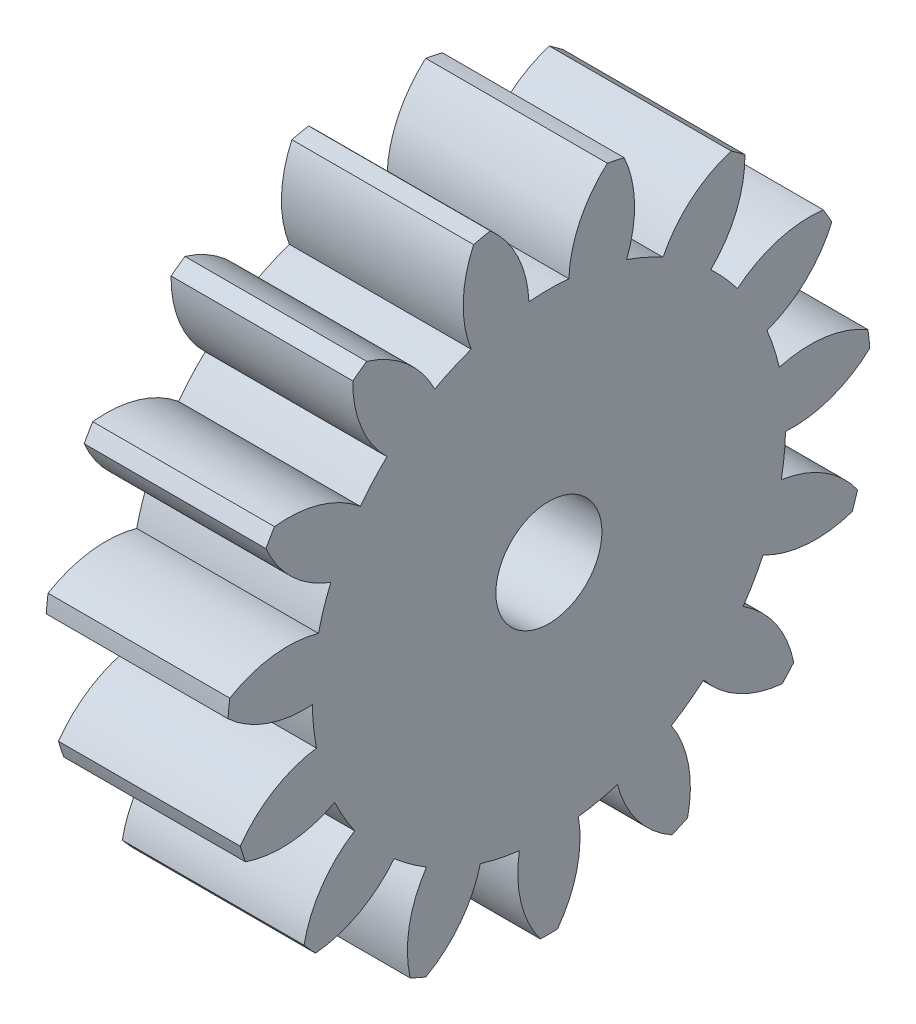
SolidWorks part; units mm, degrees
ref_plane "Plane1" through (0, 0, 0) normal (0, 0, 1) x (1, 0, 0)
ref_plane "Plane2" through (0, 0, 0) normal (0, 1, 0) x (1, 0, 0)
ref_plane "Plane3" through (0, 0, 0) normal (1, 0, 0) x (0, 0, -1)
other "Configuration Table"
sketch "HoldingSke" plane through (0, 0, 0) normal (0, 1, 0) x (1, 0, 0)
  line L0 (0, 0) -> (0.3864, -0.1035)
  line L1 (-15, 0) -> (100, 0) construction
  line L2 (0, 0) -> (-2.1039, 2.3779)
  line L3 (0, 0) -> (-11.863, 4.5341)
  line L4 (0, 0) -> (8.3417, 2.2352)
  line L5 (0, 0) -> (-46.8476, -17.4728)
  line L6 (0, 0) -> (-9.9476, -6.7116)
  line L7 (-2.1039, 2.3779) -> (8.6586, 51.2059)
  line L8 (-76.2, 54.61) -> (-75.2, 54.61)
  line L9 (-71.009, 38.7566) -> (-53.1078, 45.2721)
  line L10 (-76.2, 71.12) -> (104.1128, 71.12)
  line L11 (0, 0) -> (-12, 0)
  line L12 (-76.2, 101.6) -> (-76.113, 101.6)
  line L13 (24.9733, 27.94) -> (52.9518, 28.4284)
  line L14 (24.9733, 27.94) -> (24.9743, 27.94)
  line L15 (24.9733, 27.94) -> (100.4006, 29.5858)
  line L16 (-63.627, -2.5) -> (-12.827, -2.5)
  circle A0 centre (0, 0) radius 3.5
  circle A1 centre (0, 0) radius 15.624
  circle A2 centre (0, 0) radius 37.5
  circle A3 centre (0, 0) radius 3.5
  dimension "Hub_dia" = 75
  dimension "Bore" = 7
  dimension "MBD" = 7
  dimension "Num_teeth" = 15
  dimension "Overall_len" = 50
  dimension "Show_teeth" = 15
  dimension "Thickness" = 12
  dimension "OAL" = 50.0001
  dimension "T_dim" = 1
  dimension "Ap" = 20
  dimension "H" = 19.05
  dimension "Pitch_radius" = 180.3128
  dimension "Width" = 12
  dimension "Addendum_fac" = 1
  dimension "Dedendum_fac" = 1.25
  dimension "Clearance_fac" = 0.25
  dimension "Dedendum_add" = 0.001
sketch "BasProSke" plane through (0, 0, 0) normal (0, 1, 0) x (1, 0, 0)
  line L0 (-10, 0) -> (60, 0) construction
  line L1 (0, 0) -> (0, 21.25)
  line L2 (0, 0) -> (12, 0)
  line L3 (12, 0) -> (12, 21.25)
  line L4 (12, 21.25) -> (0, 21.25)
  dimension "Thickness" = 12
revolve "Base-Revolve" add sketch "BasProSke" angle 360 about L0
sketch "TooCutSke" plane through (0, 0, 0) normal (1, 0, 0) x (0, 0, -1)
  line L1 (0, 0) -> (0, 107) construction
  line L2 (0, 0) -> (-2.112, 18.6307) construction
  line L3 (0, 0) -> (-7.7604, 36.5097) construction
  line L4 (-2.112, 18.6307) -> (-3.8802, 18.2548) construction
  arc A0 (1.3173, 15.5684) -> (-1.3173, 15.5684) centre (0, 0) ccw
  arc A1 (3.8889, 20.917) -> (-3.8889, 20.917) centre (0, 0) ccw
  circle A2 centre (0, 0) radius 18.75 construction
  circle A3 centre (0, 0) radius 17.6192 construction
  arc A4 (-1.3173, 15.5684) -> (-3.8889, 20.917) centre (-8.8109, 15.258) ccw
  arc A5 (3.8889, 20.917) -> (1.3173, 15.5684) centre (8.8109, 15.258) ccw
  dimension "Half_ang" = 12
extrude "ToothCut" cut sketch "TooCutSke" along normal through all
fillet "Breaks" [suppressed] radius 0.05
fillet "RootFillets" [suppressed] radius 0.626
pattern_circular "TeethCuts" count 15 every 24 about axis through (-10, 0, 0) along (1, 0, 0) of "ToothCut", "RootFillets", "Breaks"
sketch "HubNeaOneSke" plane through (0, 0, 0) normal (-1, 0, 0) x (0, 0, 1)
  circle A0 centre (0, 0) radius 15.624
extrude "HubNearOne" [suppressed] add sketch "HubNeaOneSke" along normal blind 38.0001
sketch "HubNeaBotSke" plane through (0, 0, 0) normal (-1, 0, 0) x (0, 0, 1)
  circle A0 centre (0, 0) radius 15.624
extrude "HubNearBoth" [suppressed] add sketch "HubNeaBotSke" along normal blind 19
ref_plane "FarPln" through (12, 0, 0) normal (1, 0, 0) x (0, 0, -1)
sketch "HubFarSke" plane through (12, 0, 0) normal (1, 0, 0) x (0, 0, -1)
  circle A0 centre (0, 0) radius 15.624
extrude "HubFar" [suppressed] add sketch "HubFarSke" along normal blind 19
sketch "BorSke" plane through (0, 0, 0) normal (1, 0, 0) x (0, 0, -1)
  circle A0 centre (0, 0) radius 3.5
  dimension "Diameter" = 7
extrude "Bore" cut sketch "BorSke" along normal mid plane 100.0001
sketch "KeySke" plane through (0, 0, 0) normal (1, 0, 0) x (0, 0, -1)
  line L0 (-1, 0) -> (-1, 4.5)
  line L1 (-1, 4.5) -> (1, 4.5)
  line L2 (1, 4.5) -> (1, 0)
  line L3 (0, 0) -> (0, 34) construction
  line L4 (-1, 0) -> (1, 0)
  dimension "Offset" = 4.5
  dimension "Width" = 2
extrude "Keyway" [suppressed] cut sketch "KeySke" along normal mid plane 100.0001
pattern_circular "Keyway2" [suppressed] count 2 every 90 about axis through (-10, 0, 0) along (1, 0, 0)
equation "' \"Module@HoldingSke\" = 6.35"
equation "' \"Num_teeth@HoldingSke\" = 12"
equation "' \"Ap@HoldingSke\" =  20"
equation "' \"Ap@HoldingSke\" = 20"
equation "' \"Width@HoldingSke\" = 0.5 * 25.4"
equation "' \"Hub_dia@HoldingSke\"= 1 * 25.4"
equation "' \"Hub_dia@HoldingSke\" = 1 * 25.4"
equation "' \"Overall_len@HoldingSke\" = 1.0 * 25.4"
equation "' \"Bore@HoldingSke\" = 0.75 * 25.4"
equation "' \"T_dim@HoldingSke\" = 0.1 * 25.4"
equation "' \"Width@KeySke\" = 0.25 * 25.4"
equation "' \"Show_teeth@HoldingSke\" = 13"
equation "' \"Backlash@HoldingSke\" = 0.009 * 25.4"
equation "' \"Addendum_fac@HoldingSke\" = 1.0"
equation "' \"Dedendum_fac@HoldingSke\" = 1.25"
equation "' \"Dedendum_add@HoldingSke\" = 0.00005 * 25.4"
equation "' \"Clearance_fac@HoldingSke\" = 0.25"
equation "\"Pitch@HoldingSke\" = 1 / \"Module@HoldingSke\""
equation "\"Overcut_dia@TooCutSke\" = (\"Num_teeth@HoldingSke\" + 2 * \"Addendum_fac@HoldingSke\") / \"Pitch@HoldingSke\" + 0.002 * 25.4"
equation "\"Pitch_dia@TooCutSke\" = \"Num_teeth@HoldingSke\" / \"Pitch@HoldingSke\""
equation "\"Base_dia@TooCutSke\" = \"Num_teeth@HoldingSke\" / \"Pitch@HoldingSke\" * cos((\"Ap@HoldingSke\"  * 3.14159265 / 180))"
equation "\"Root_dia@TooCutSke\" = (\"Num_teeth@HoldingSke\" + 2) / \"Pitch@HoldingSke\" - 2 * (\"Addendum_fac@HoldingSke\" + \"Dedendum_fac@HoldingSke\") / \"Pitch@HoldingSke\" - \"Dedendum_add@HoldingSke\" * 2"
equation "\"Half_ang@TooCutSke\" = 180 / \"Num_teeth@HoldingSke\""
equation "\"Half_CT@TooCutSke\" = \"Num_teeth@HoldingSke\" / \"Pitch@HoldingSke\" * sin((3.14159265 / 2 / \"Num_teeth@HoldingSke\")) / 2 - 7 * \"Backlash@HoldingSke\" / 4"
equation "\"Flank_rad@TooCutSke\" = \"Num_teeth@HoldingSke\" / \"Pitch@HoldingSke\" / 5"
equation "\"Radius@RootFillets\" = \"Clearance_fac@HoldingSke\" / \"Pitch@HoldingSke\" + \"Dedendum_add@HoldingSke\""
equation "\"Break_rad@Breaks\" = 0.02 / \"Pitch@HoldingSke\""
equation "\"Thickness@HoldingSke\" = \"Width@HoldingSke\""
equation "\"OAL@HoldingSke\" = \"Thickness@HoldingSke\""
equation "\"MHD@HoldingSke\" = (\"Num_teeth@HoldingSke\" + 2) / \"Pitch@HoldingSke\" - 2 * (\"Addendum_fac@HoldingSke\" + \"Dedendum_fac@HoldingSke\")  / \"Pitch@HoldingSke\" - \"Dedendum_add@HoldingSke\" * 2"
equation "\"MBD@HoldingSke\" = (\"Num_teeth@HoldingSke\" + 2) / \"Pitch@HoldingSke\" - 2 * (\"Addendum_fac@HoldingSke\" + \"Dedendum_fac@HoldingSke\")  / \"Pitch@HoldingSke\" - \"Dedendum_add@HoldingSke\" * 2 - 0.002 * 25.4"
equation "\"MHD@HoldingSke\" = ((sgn( \"MHD@HoldingSke\" - \"Hub_dia@HoldingSke\" )-1)*( \"MHD@HoldingSke\" - \"Hub_dia@HoldingSke\" ))/-2+ \"Hub_dia@HoldingSke\""
equation "\"MBD@HoldingSke\" = ((sgn( \"MBD@HoldingSke\" - \"Bore@HoldingSke\" )-1)*( \"MBD@HoldingSke\" - \"Bore@HoldingSke\" ))/-2+ \"Bore@HoldingSke\""
equation "\"OAL@HoldingSke\" = ((sgn( \"OAL@HoldingSke\" - \"Overall_len@HoldingSke\" )+1)*( \"OAL@HoldingSke\" - \"Overall_len@HoldingSke\" ))/2 + \"Overall_len@HoldingSke\" + 0.000002 * 25.4"
equation "\"Num_teeth@TeethCuts\" = int( \"Show_teeth@HoldingSke\" ) + 1"
equation "\"Num_teeth@TeethCuts\" = ((sgn( \"Num_teeth@TeethCuts\" - \"Num_teeth@HoldingSke\" )-1)*( \"Num_teeth@TeethCuts\" - \"Num_teeth@HoldingSke\" ))/-2+ \"Num_teeth@HoldingSke\""
equation "\"Num_teeth@TeethCuts\" = ((sgn( \"Num_teeth@TeethCuts\" - 2.0)+1)*( \"Num_teeth@TeethCuts\" - 2.0))/2 +2.0"
equation "\"Angle@TeethCuts\" = 360.0 / \"Num_teeth@HoldingSke\""
equation "\"Diameter@BasProSke\" = (\"Num_teeth@HoldingSke\" + 2 * \"Addendum_fac@HoldingSke\") / \"Pitch@HoldingSke\""
equation "\"Thickness@BasProSke\"  = \"Thickness@HoldingSke\""
equation "' \"Fillet_rad@BasProSke\" =  \"Thickness@HoldingSke\" * 0.05"
equation "' \"Fillet_rad@BasProSke\" = \"Thickness@HoldingSke\" * 0.05"
equation "\"MHD@HoldingSke\" = ((sgn( \"MHD@HoldingSke\" - \"Root_dia@TooCutSke\" )-1)*( \"MHD@HoldingSke\" - \"Root_dia@TooCutSke\" ))/-2+ \"Root_dia@TooCutSke\""
equation "\"Diameter@HubNeaOneSke\" = \"MHD@HoldingSke\""
equation "\"Length@HubNearOne\" = \"OAL@HoldingSke\" - \"Thickness@BasProSke\""
equation "\"Diameter@HubNeaBotSke\" = \"MHD@HoldingSke\""
equation "\"Length@HubNearBoth\" = ( \"OAL@HoldingSke\" - \"Thickness@BasProSke\" ) / 2.0"
equation "\"Thickness@FarPln\" = \"Thickness@BasProSke\""
equation "\"Diameter@HubFarSke\" = \"MHD@HoldingSke\""
equation "\"Length@HubFar\" = ( \"OAL@HoldingSke\" - \"Thickness@BasProSke\" ) / 2.0"
equation "\"Diameter@BorSke\" = \"MBD@HoldingSke\""
equation "\"D1@Bore\" = \"OAL@HoldingSke\" * 2.0"
equation "\"D1@Keyway\" = \"OAL@HoldingSke\" * 2.0"
equation "\"Offset@KeySke\" = \"T_dim@HoldingSke\" + \"MBD@HoldingSke\" / 2.0"
